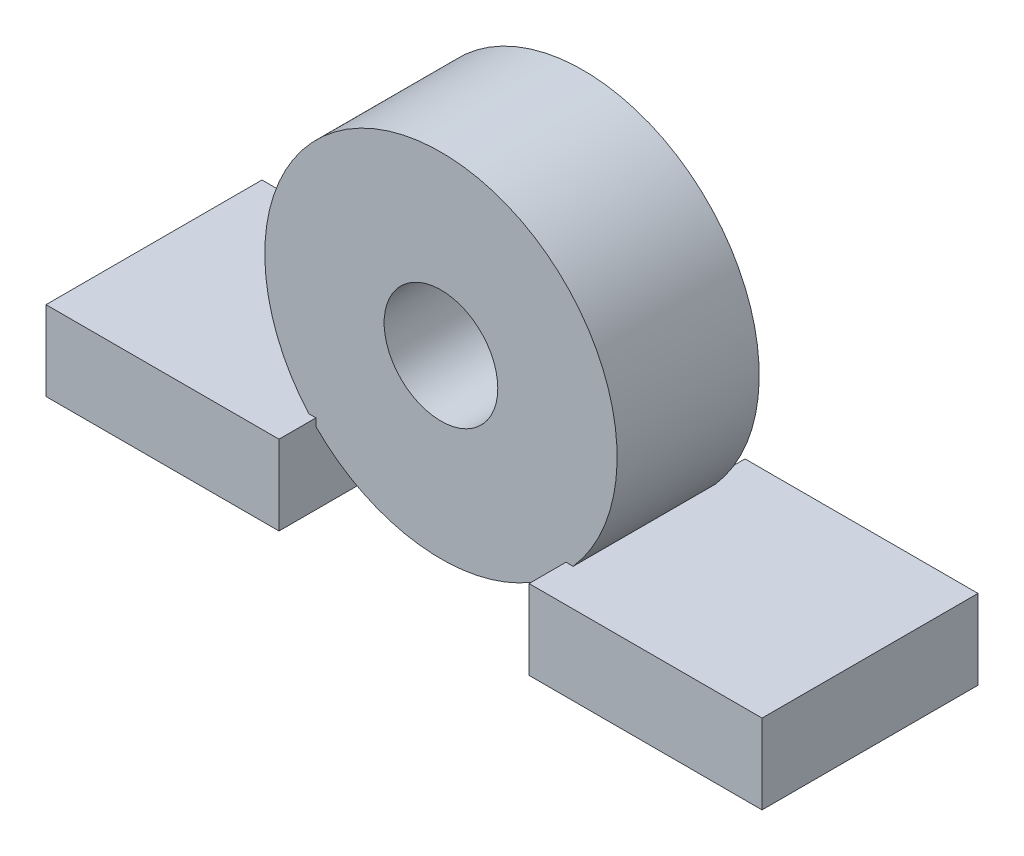
SolidWorks part; units mm, degrees
ref_plane "Спереди" through (0, 0, 0) normal (0, 0, 1) x (1, 0, 0)
ref_plane "Сверху" through (0, 0, 0) normal (0, 1, 0) x (1, 0, 0)
ref_plane "Справа" through (0, 0, 0) normal (1, 0, 0) x (0, 0, -1)
ref_plane "Плоскость2" through (0, -36, 0) normal (0, 1, 0) x (-1, 0, 0)
sketch "Эскиз13" plane through (0, -36, 0) normal (0, 1, 0) x (-1, 0, 0)
  line L2 (-28, 36.5) -> (13, 36.5)
  line L6 (13, -1.5) -> (13, 36.5)
  line L7 (-72, -1.5) -> (-113, -1.5)
  line L8 (-72, 36.5) -> (-113, 36.5)
  line L9 (-113, -1.5) -> (-113, 36.5)
  line L10 (-72, -1.5) -> (-72, 36.5)
  line L11 (-28, -1.5) -> (13, -1.5)
  line L12 (-28, -1.5) -> (-28, 36.5)
  dimension "D5" = 41
  dimension "D6" = 38
  dimension "D7" = 44
  dimension "D8" = 41
  dimension "D9" = 38
  dimension "D12" = 41
  dimension "D13" = 38
  dimension "D14" = 38
  dimension "D15" = 41
  dimension "D16" = 13
  dimension "D17" = 113
  dimension "D27" = 36.5
  dimension "D28" = 36.5
ref_plane "Plane1" through (0, 0, 5) normal (0, 0, 1) x (1, 0, 0)
sketch "Sketch1" plane through (0, 0, 5) normal (0, 0, 1) x (1, 0, 0)
  circle A0 centre (50, -1.5) radius 10
  circle A1 centre (50, -1.5) radius 31
  dimension "D1" = 20
  dimension "D2" = 62
extrude "Boss-Extrude1" add sketch "Эскиз13" along normal blind 14
extrude "Boss-Extrude2" add sketch "Sketch1" along normal blind 25
